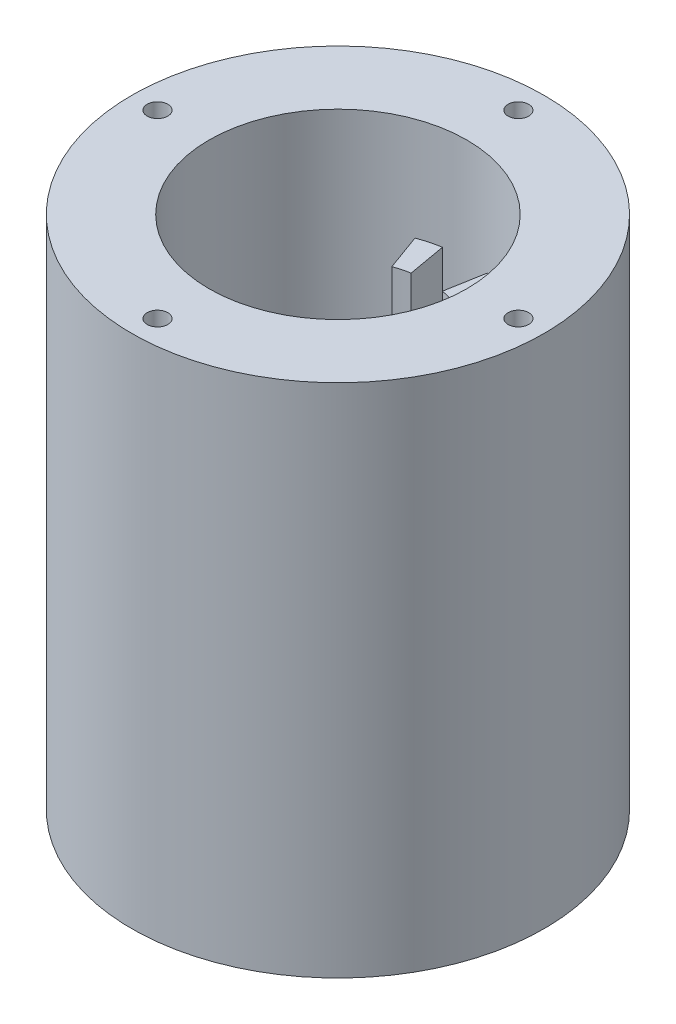
SolidWorks part; units mm, degrees
ref_plane "Front Plane" through (0, 0, 0) normal (0, 0, 1) x (1, 0, 0)
ref_plane "Top Plane" through (0, 0, 0) normal (0, 1, 0) x (1, 0, 0)
ref_plane "Right Plane" through (0, 0, 0) normal (1, 0, 0) x (0, 0, -1)
sketch "Sketch1" plane through (0, 0, 0) normal (0, 1, 0) x (1, 0, 0)
  circle A0 centre (0, 0) radius 40
  circle A1 centre (0, 0) radius 25
  dimension "D1" = 80
  dimension "D2" = 50
extrude "Boss-Extrude1" add sketch "Sketch1" along normal mid plane 100
sketch "Sketch2" plane through (0, 50, 0) normal (0, 1, 0) x (1, 0, 0)
  circle A0 centre (0, 35) radius 2
  circle A1 centre (35, 0) radius 2
  circle A2 centre (0, -35) radius 2
  circle A3 centre (-35, 0) radius 2
  point P12 (0, 0)
  dimension "D1" = 4
  dimension "D2" = 35
  dimension "D3" = 4
extrude "Cut-Extrude1" cut sketch "Sketch2" against normal blind 10
mirror "Mirror1" about plane through (0, 0, 0) normal (0, 1, 0) of "Cut-Extrude1"
sketch "Sketch3" plane through (0, -50, 0) normal (0, -1, 0) x (1, 0, 0)
  line L0 (0, 0) -> (0, 25) construction
  line L1 (0, 0) -> (4.3412, 24.6202)
  line L2 (0, 0) -> (-4.3412, 24.6202)
  line L3 (0, 0) -> (8.5505, 23.4923)
  line L4 (0, 0) -> (-8.5505, 23.4923)
  circle A0 centre (0, 0) radius 25 construction
  circle A1 centre (0, 0) radius 25
  circle A2 centre (0, 0) radius 17.5
  circle M13 centre (0, 0) radius 25
  dimension "D3" = 35
  dimension "D1" = 10
  dimension "D2" = 10
  dimension "D4" = 20
  dimension "D5" = 160
extrude "Boss-Extrude2" add sketch "Sketch3" against normal blind 50 from offset 30 contours A2 L2 L4 M13 | A2 L3 L1 M13 offset against normal yes
mirror "Mirror2" about plane through (0, 0, 0) normal (0, 0, 1) of "Boss-Extrude2"
